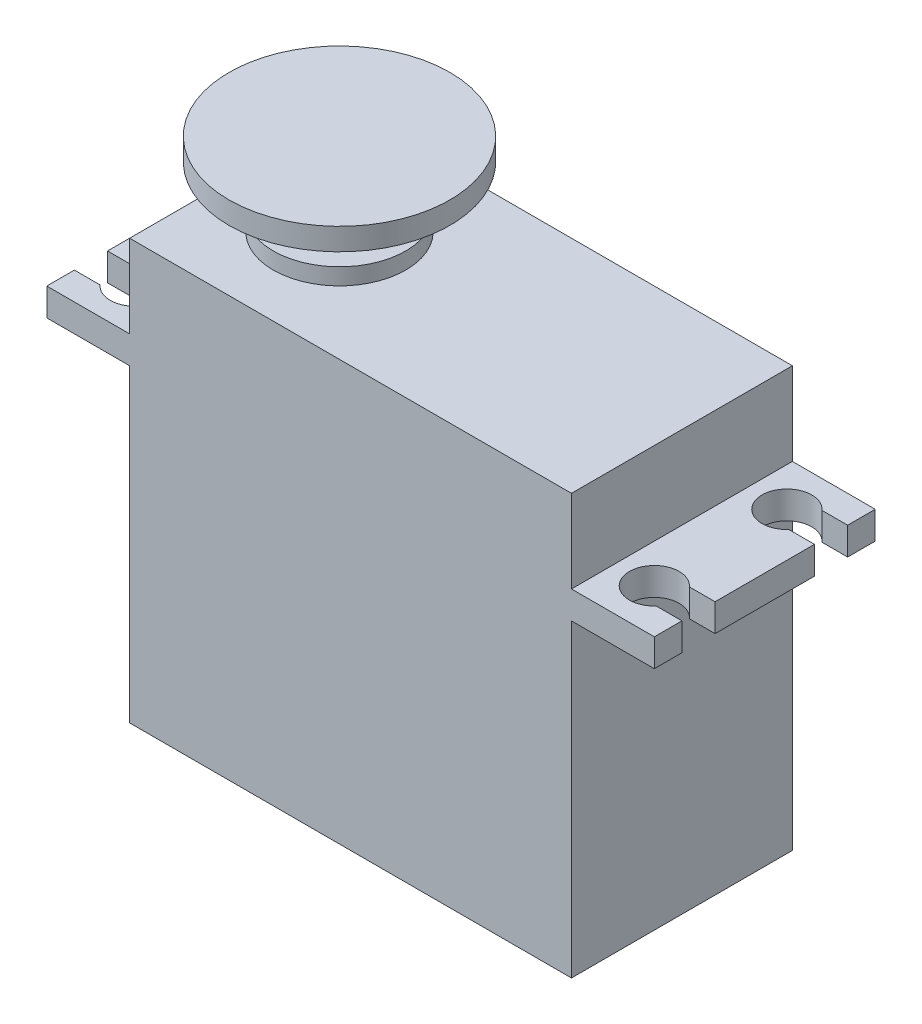
SolidWorks part; units mm, degrees
material "Custom Plastic"
ref_plane "Front Plane" through (0, 0, 0) normal (0, 0, 1) x (1, 0, 0)
ref_plane "Top Plane" through (0, 0, 0) normal (0, 1, 0) x (1, 0, 0)
ref_plane "Right Plane" through (0, 0, 0) normal (1, 0, 0) x (0, 0, -1)
sketch "Sketch1" plane through (0, 0, 0) normal (0, 1, 0) x (1, 0, 0)
  line L1 (-20, 10) -> (20, 10)
  line L2 (-20, 10) -> (-20, -10)
  line L3 (-20, -10) -> (20, -10)
  line L4 (20, 10) -> (20, -10)
  line L5 (-20, 10) -> (20, -10) construction
  line L6 (-20, -10) -> (20, 10) construction
  point P0 (0, 0)
  dimension "D1" = 40
  dimension "D2" = 20
extrude "Boss-Extrude1" add sketch "Sketch1" along normal blind 38
sketch "Sketch2" plane through (20, 0, 0) normal (1, 0, 0) x (0, 0, -1)
  line L0 (-10, 28) -> (10, 28)
  line L1 (-10, 38) -> (-10, 0) construction
  line L2 (10, 38) -> (10, 0) construction
  line L3 (-10, 0) -> (10, 0) construction
  line L4 (10, 28) -> (10, 30.5)
  line L5 (10, 30.5) -> (-10, 30.5)
  line L6 (-10, 30.5) -> (-10, 28)
  dimension "D1" = 28
  dimension "D2" = 2.5
extrude "Boss-Extrude2" add sketch "Sketch2" along normal blind 7.5
sketch "Sketch3" plane through (0, 30.5, 0) normal (0, 1, 0) x (1, 0, 0)
  line L0 (20, -0.5478) -> (20, 0.4522)
  line L1 (20, 10) -> (20, -10) construction
  line L2 (20, 0.4522) -> (27.5, 0.4522)
  line L3 (27.5, 10) -> (27.5, -10) construction
  line L4 (27.5, 0.4522) -> (27.5, -0.5478)
  line L5 (27.5, -0.5478) -> (20, -0.5478)
  line L6 (27.5, -10) -> (20, -10) construction
  line L7 (27.5, 10) -> (20, 10) construction
  line L8 (27.5, -7.5) -> (25.1771, -7.5)
  line L9 (27.5, -4.5) -> (25.1771, -4.5)
  arc A0 (25.1771, -4.5) -> (25.1771, -7.5) centre (23.5, -6) ccw
  point P5 (20, -0.0478)
  point P8 (23.5, -6)
  point P10 (23.5, 6)
  point P17 (27.5, -7.5)
  point P21 (27.5, -4.5)
  dimension "D6" = 4.5
  dimension "D1" = 1
  dimension "D2" = 4
  dimension "D3" = 4
  dimension "D4" = 4
  dimension "D5" = 4
  dimension "D7" = 1.5
  dimension "D8" = 1.5
extrude "Cut-Extrude1" cut sketch "Sketch3" against normal through all contours A0
mirror "Mirror1" about plane through (0, 0, 0) normal (0, 0, 1) of "Cut-Extrude1"
mirror "Mirror2" about plane through (0, 0, 0) normal (1, 0, 0) of "Cut-Extrude1", "Boss-Extrude2", "Mirror1"
sketch "Sketch4" plane through (0, 38, 0) normal (0, 1, 0) x (1, 0, 0)
  line L0 (-20, 10) -> (-20, -10) construction
  circle A0 centre (-11, 0) radius 6
  point P0 (-11, 0)
  dimension "D2" = 12
  dimension "D1" = 9
extrude "Boss-Extrude3" add sketch "Sketch4" along normal blind 1.5
sketch "Sketch6" plane through (0, 39.5, 0) normal (0, 1, 0) x (1, 0, 0)
  circle A0 centre (-11, 0) radius 4
extrude "Boss-Extrude4" add sketch "Sketch6" along normal blind 2
sketch "Sketch7" plane through (0, 41.5, 0) normal (0, 1, 0) x (1, 0, 0)
  circle A0 centre (-11, 0) radius 4.5
  dimension "D1" = 9
extrude "Boss-Extrude5" add sketch "Sketch7" along normal blind 2
sketch "Sketch8" plane through (0, 43.5, 0) normal (0, 1, 0) x (1, 0, 0)
  circle A0 centre (-11, 0) radius 10
  point P0 (-11, 0)
  dimension "D1" = 20
extrude "Boss-Extrude6" add sketch "Sketch8" along normal blind 2
